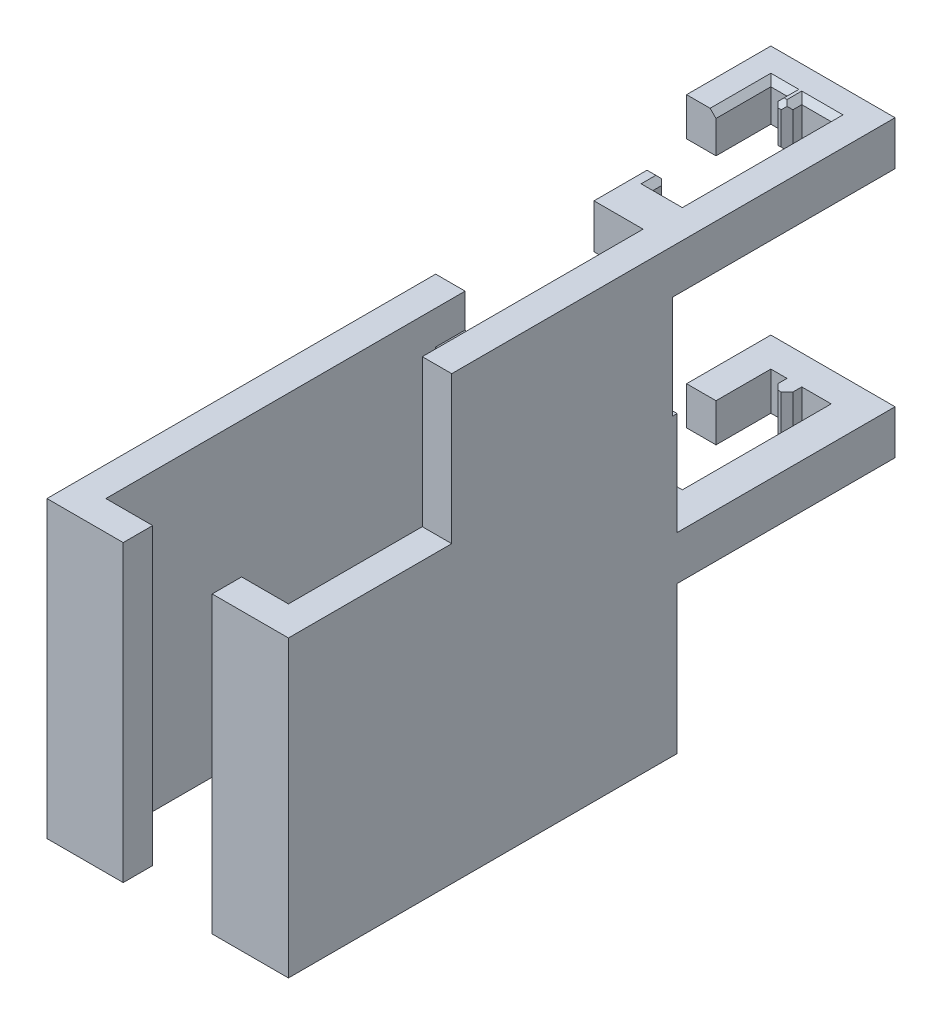
SolidWorks part; units mm, degrees
ref_plane "Front Plane" through (0, 0, 0) normal (0, 0, 1) x (1, 0, 0)
ref_plane "Top Plane" through (0, 0, 0) normal (0, 1, 0) x (1, 0, 0)
ref_plane "Right Plane" through (0, 0, 0) normal (1, 0, 0) x (0, 0, -1)
sketch "Sketch1" plane through (0, 0, 0) normal (0, 1, 0) x (1, 0, 0)
  line L0 (0, 0) -> (0, -2) construction
  line L1 (0, 0) -> (12.4, 0)
  line L2 (0, 0) -> (0, 22.4)
  line L3 (0, 22.4) -> (12.4, 22.4)
  line L4 (12.4, 0) -> (12.4, 22.4)
  line L5 (0, -2) -> (-2, -2) construction
  line L6 (12.4, 22.4) -> (12.4, 24.4) construction
  line L7 (12.4, 24.4) -> (14.4, 24.4) construction
  line L9 (-2, -2) -> (14.4, -2)
  line L10 (-2, -2) -> (-2, 24.4)
  line L11 (-2, 24.4) -> (14.4, 24.4)
  line L12 (14.4, -2) -> (14.4, 24.4)
  dimension "D1" = 22.4
  dimension "D2" = 12.4
  dimension "D3" = 2
  dimension "D4" = 2
  dimension "D5" = 2
  dimension "D6" = 2
extrude "Boss-Extrude1" add sketch "Sketch1" along normal blind 20
sketch "Sketch2" plane through (0, 0, -24.4) normal (0, 0, -1) x (-1, 0, 0)
  line L0 (-12.4, 20) -> (-12.4, 17.7121)
  line L1 (-12.4, 17.7121) -> (-10.5445, 15.8566)
  line L2 (-10.5445, 15.8566) -> (-9.2581, 15.2935)
  line L3 (-9.2581, 15.2935) -> (-9.2581, 13.7641)
  line L4 (-9.2581, 13.7641) -> (-8.0844, 12.5904)
  line L5 (-8.0844, 12.5904) -> (-6.2, 11.7656)
  line L6 (-6.2, 11.7656) -> (-6.2, 17.9966) construction
  line L7 (-4.3156, 12.5904) -> (-6.2, 11.7656)
  line L8 (-3.1419, 13.7641) -> (-4.3156, 12.5904)
  line L9 (-3.1419, 15.2935) -> (-3.1419, 13.7641)
  line L10 (-1.8555, 15.8566) -> (-3.1419, 15.2935)
  line L11 (0, 17.7121) -> (-1.8555, 15.8566)
  line L12 (0, 20) -> (0, 17.7121)
  line L13 (-12.4, 20) -> (0, 20)
extrude "Cut-Extrude1" cut sketch "Sketch2" against normal blind 10
ref_plane "Plane2" through (0, 30, 0) normal (0, 1, 0) x (1, 0, 0)
sketch "Sketch4" plane through (0, 30, 0) normal (0, 1, 0) x (1, 0, 0)
  line L0 (12.4, 0) -> (12.4, 24.4) construction
  line L1 (12.4, 12.2) -> (14.4, 12.2)
  line L2 (12.4, 12.2) -> (12.4, 24.0875)
  line L3 (12.4727, 39.1975) -> (14.4, 39.1975)
  line L4 (14.4, 12.2) -> (14.4, 39.1975)
  line L5 (7.965, 39.1975) -> (7.965, 37.1975) construction
  line L6 (12.4727, 39.1975) -> (7.965, 39.1975)
  line L7 (12.065, 27.0875) -> (10.065, 27.0875)
  line L8 (12.065, 37.1975) -> (10.065, 37.1975)
  line L9 (12.065, 37.1975) -> (12.065, 27.0875)
  line L10 (7.965, 39.1975) -> (5.965, 39.1975)
  line L11 (7.965, 37.1975) -> (7.965, 33.4736)
  line L12 (7.965, 33.4736) -> (5.965, 33.4736)
  line L13 (5.965, 39.1975) -> (5.965, 33.4736)
  line L14 (10.065, 27.0875) -> (10.065, 28.0875)
  line L15 (10.065, 28.0875) -> (9.065, 28.0875)
  line L16 (9.065, 36.1975) -> (9.065, 37.1975)
  line L17 (9.065, 28.0875) -> (9.065, 24.0875)
  line L18 (9.065, 24.0875) -> (12.4, 24.0875)
  line L19 (10.065, 27.0875) -> (10.065, 24.0875) construction
  line L20 (12.065, 36.0975) -> (12.065, 35.9975) construction
  line L21 (10.065, 28.0875) -> (10.065, 28.0975) construction
  line L22 (12.065, 28.0975) -> (9.065, 28.0975) construction
  line L23 (12.065, 36.0975) -> (12.065, 37.1975) construction
  line L24 (12.065, 32.1425) -> (11.2796, 32.1425) construction
  line L25 (10.065, 36.1975) -> (9.065, 36.1975)
  line L26 (10.065, 37.1975) -> (10.065, 36.1975)
  line L27 (9.065, 37.1975) -> (7.965, 37.1975)
  dimension "D1" = 2
  dimension "D2" = 2
  dimension "D3" = 2
  dimension "D4" = 1
  dimension "D5" = 1
  dimension "D6" = 2
  dimension "D7" = 3
  dimension "D8" = 4.1
  dimension "D9" = 0.1
  dimension "D10" = 0.01
  dimension "D11" = 1.1
extrude "Boss-Extrude2" add sketch "Sketch4" against normal blind 3 separate body
chamfer "Chamfer3" distance 0.4 angle 45 11 edges at (6.965, 27, -33.4736) (7.965, 27, -35.3356) (8.515, 27, -37.1975) (9.065, 27, -36.6975) (9.565, 27, -36.1975) (10.065, 27, -36.6975) (11.065, 27, -37.1975) (9.565, 27, -28.0875) (10.065, 27, -27.5875) (11.065, 27, -27.0875) (12.065, 27, -32.1425)
sketch "Sketch5" plane through (0, 30, 0) normal (0, 1, 0) x (1, 0, 0)
  line L0 (14.4, -2) -> (14.4, 24.4) construction
  line L1 (12.4, 24.0875) -> (14.4, 24.0875)
  line L2 (12.4, 24.0875) -> (12.4, 9.09)
  line L3 (12.4, 9.09) -> (14.4, 9.09)
  line L4 (14.4, 24.0875) -> (14.4, 9.09)
extrude "Boss-Extrude3" add sketch "Sketch5" against normal blind 10
pattern_linear "LPattern1" count 2 spacing 17 along (0, -1, 0) of "Boss-Extrude2"
chamfer "Chamfer1" distance 0.4 angle 45 10 edges at (9.565, 30, -28.0875) (10.065, 30, -27.5875) (7.965, 30, -35.3356) (8.515, 30, -37.1975) (9.065, 30, -36.6975) (9.565, 30, -36.1975) (10.065, 30, -36.6975) (11.065, 30, -27.0875) (11.065, 30, -37.1975) (12.065, 30, -32.1425)
chamfer "Chamfer5" distance 0.4 angle 45 9 edges at (6.965, 10, -33.4736) (7.965, 10, -35.3356) (8.515, 10, -37.1975) (9.065, 10, -36.6975) (9.565, 10, -36.1975) (10.065, 10, -36.6975) (11.065, 10, -37.1975) (12.065, 10, -32.1425) (11.065, 10, -27.0875)
chamfer "Chamfer6" distance 0.4 angle 45 7 edges at (9.065, 28.5, -28.0875) (10.065, 28.5, -28.0875) (10.065, 28.5, -36.1975) (9.065, 28.5, -36.1975) (10.065, 11.7, -36.1975) (9.065, 11.7, -36.1975) (9.065, 11.5, -28.0875)
sketch "Sketch6" plane through (0, 20, 0) normal (0, 1, 0) x (1, 0, 0)
  line L0 (3.1789, 0) -> (3.1789, -2)
  line L1 (0, 0) -> (12.4, 0) construction
  line L2 (-2, -2) -> (14.4, -2) construction
  line L3 (0, 0) -> (12.4, 0) construction
  line L4 (6.2, 0) -> (6.2, -2) construction
  line L5 (9.2211, 0) -> (9.2211, -2)
  line L6 (3.1789, 0) -> (3.1789, -2)
  line L7 (3.1789, -2) -> (9.2211, -2)
  line L8 (3.1789, 0) -> (9.2211, 0)
  line M5 (12.4, 0) -> (0, 0)
  line M9 (-2, -2) -> (14.4, -2)
extrude "Cut-Extrude2" cut sketch "Sketch6" against normal through all and the other way through all contours L5 L0 M5 M9
